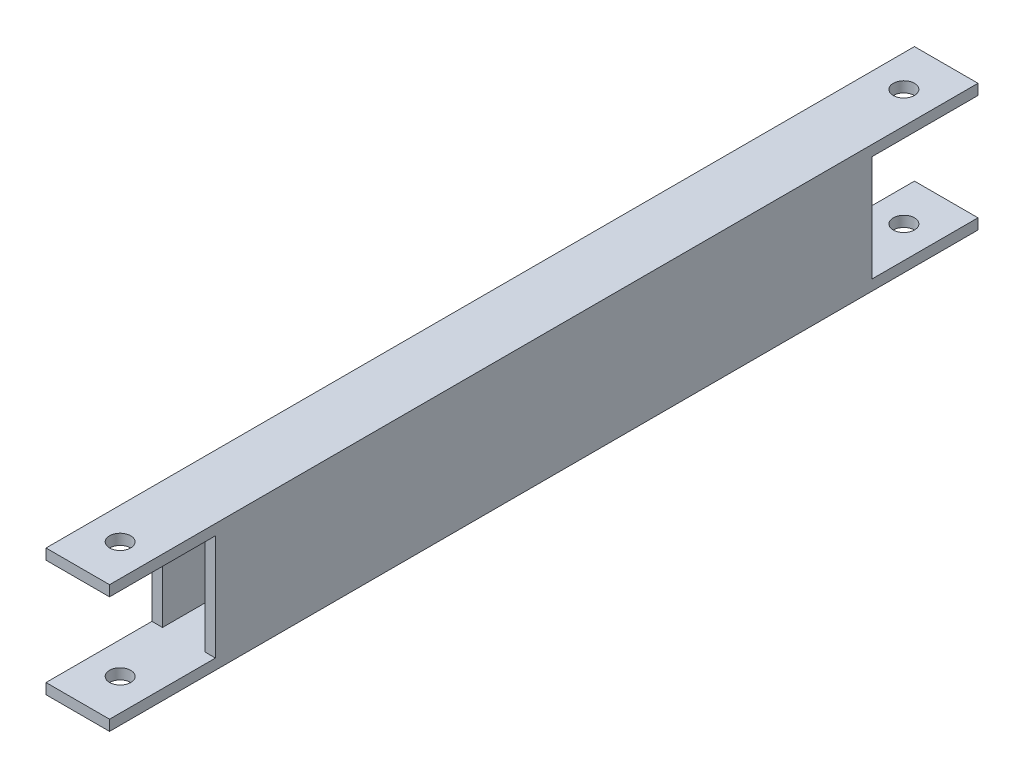
SolidWorks part; units mm, degrees
ref_plane "Front Plane" through (0, 0, 0) normal (0, 0, 1) x (1, 0, 0)
ref_plane "Top Plane" through (0, 0, 0) normal (0, 1, 0) x (1, 0, 0)
ref_plane "Right Plane" through (0, 0, 0) normal (1, 0, 0) x (0, 0, -1)
sketch "Sketch1" plane through (0, 0, 0) normal (0, 0, 1) x (1, 0, 0)
  line L0 (15.875, 3.175) -> (15.875, 34.925)
  line L1 (0, 0) -> (19.05, 0)
  line L2 (0, 0) -> (0, 38.1)
  line L3 (0, 38.1) -> (19.05, 38.1)
  line L4 (19.05, 0) -> (19.05, 38.1)
  line L5 (0, 0) -> (19.05, 38.1) construction
  line L6 (0, 38.1) -> (19.05, 0) construction
  line L7 (3.175, 34.925) -> (15.875, 34.925)
  line L8 (3.175, 3.175) -> (3.175, 34.925)
  line L9 (3.175, 3.175) -> (15.875, 3.175)
  point P4 (9.525, 19.05)
  dimension "D1" = 38.1
  dimension "D2" = 19.05
  dimension "D3" = 3.175
extrude "Boss-Extrude1" add sketch "Sketch1" along normal blind 260.35
ref_plane "Plane1" through (0, 0, 130.175) normal (0, 0, 1) x (1, 0, 0)
sketch "Sketch2" plane through (0, 0, 260.35) normal (0, 0, 1) x (1, 0, 0)
  line L0 (0, 38.1) -> (0, 0) construction
  line L1 (0, 34.925) -> (19.05, 34.925)
  line L2 (0, 34.925) -> (0, 3.175)
  line L3 (0, 3.175) -> (19.05, 3.175)
  line L4 (19.05, 34.925) -> (19.05, 3.175)
  line L5 (0, 34.925) -> (19.05, 3.175) construction
  line L6 (0, 3.175) -> (19.05, 34.925) construction
  line L7 (19.05, 0) -> (19.05, 38.1) construction
  point P4 (9.525, 19.05)
extrude "Cut-Extrude1" cut sketch "Sketch2" against normal blind 31.75
sketch "Sketch3" plane through (0, 38.1, 0) normal (0, 1, 0) x (1, 0, 0)
  line L0 (9.525, -260.35) -> (9.525, -247.65) construction
  line L1 (19.05, -260.35) -> (0, -260.35) construction
  circle A0 centre (9.525, -247.65) radius 3.175
  dimension "D2" = 6.35
  dimension "D1" = 12.7
extrude "Cut-Extrude2" cut sketch "Sketch3" against normal through all
mirror "Mirror1" about plane through (0, 0, 130.175) normal (0, 0, 1) of "Cut-Extrude2", "Cut-Extrude1"
